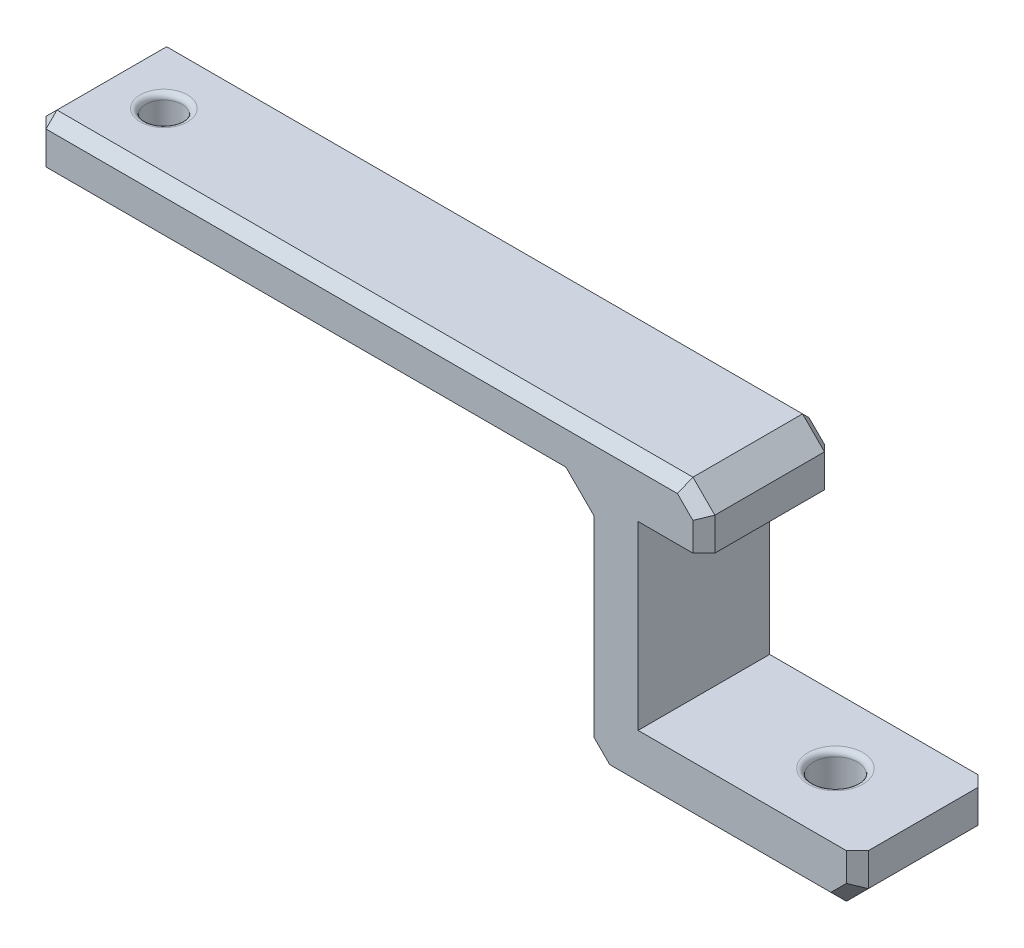
SolidWorks part; units mm, degrees
ref_plane "Plano frontal" through (0, 0, 0) normal (0, 0, 1) x (1, 0, 0)
ref_plane "Plano superior" through (0, 0, 0) normal (0, 1, 0) x (1, 0, 0)
ref_plane "Plano direito" through (0, 0, 0) normal (1, 0, 0) x (0, 0, -1)
sketch "Esboço1" plane through (0, 0, 0) normal (0, 0, 1) x (1, 0, 0)
  line L1 (19.8864, 14.25) -> (13.8864, 14.25)
  line L3 (13.8864, -2.25) -> (33.8864, -2.25)
  line L4 (33.8864, -2.25) -> (33.8864, -7.25)
  line L5 (33.8864, -7.25) -> (8.8864, -7.25)
  line L6 (8.8864, -7.25) -> (8.8864, 14.25)
  line L7 (19.8864, 19.25) -> (19.8864, 14.25)
  line L9 (13.8864, 14.25) -> (13.8864, -2.25)
  line L15 (19.8864, 19.25) -> (-41.1136, 19.25)
  line L16 (-41.1136, 19.25) -> (-41.1136, 14.25)
  line L17 (-41.1136, 14.25) -> (8.8864, 14.25)
  dimension "D1" = 5
  dimension "D2" = 20
  dimension "D3" = 16.5
  dimension "D4" = 6
  dimension "D6" = 5
  dimension "D7" = 0
  dimension "D8" = 5
  dimension "D9" = 50
extrude "Ressalto-extrusão1" add sketch "Esboço1" along normal blind 12
sketch "Esboço3" plane through (0, -7.25, 0) normal (0, -1, 0) x (1, 0, 0)
  line L0 (33.8864, 6) -> (25.8864, 6) construction
  line L1 (33.8864, 12) -> (33.8864, 0) construction
  circle A0 centre (25.8864, 6) radius 2
  dimension "D1" = 4
  dimension "D2" = 8
extrude "Corte-extrusão1" cut sketch "Esboço3" against normal blind 15
chamfer "Chanfro1" distance 1.5 angle 45 1 edges at (25.8864, -7.25, 4)
fillet "Filete1" radius 0.5 1 edges at (27.8864, -2.25, 6)
chamfer "Chanfro5" distance 2 angle 45 4 edges at (33.8864, -7.25, 6) (8.8864, -7.25, 6) (8.8864, 14.25, 6) (19.8864, 19.25, 6)
chamfer "Chanfro8" distance 1 angle 45 24 edges at (-41.1136, 19.25, 6) (-41.1136, 16.75, 12) (-41.1136, 14.25, 6) (-41.1136, 16.75, 0) (19.8864, 15.75, 0) (-11.6136, 19.25, 0) (33.8864, -3.75, 0) (32.8864, -6.25, 0) (21.3864, -7.25, 0) (9.8864, -6.25, 0) (8.8864, 3.5, 0) (7.8864, 13.25, 0) (-17.1136, 14.25, 0) (33.8864, -3.75, 12) (32.8864, -6.25, 12) (21.3864, -7.25, 12) (9.8864, -6.25, 12) (8.8864, 3.5, 12) (7.8864, 13.25, 12) (-17.1136, 14.25, 12) (19.8864, 15.75, 12) (-11.6136, 19.25, 12) (18.8864, 18.25, 0) (18.8864, 18.25, 12)
sketch "Esboço4" plane through (0, 19.25, 0) normal (0, 1, 0) x (1, 0, 0)
  line L0 (-40.1136, -6) -> (-35.3636, -6) construction
  line L1 (-40.1136, -1) -> (-40.1136, -11) construction
  circle A0 centre (-35.3636, -6) radius 1.65
  dimension "D1" = 3.3
  dimension "D2" = 4.75
extrude "Corte-extrusão2" cut sketch "Esboço4" against normal blind 10
fillet "Filete2" radius 0.5 2 edges at (-37.0136, 14.25, 6) (-35.3636, 19.25, 7.65)
